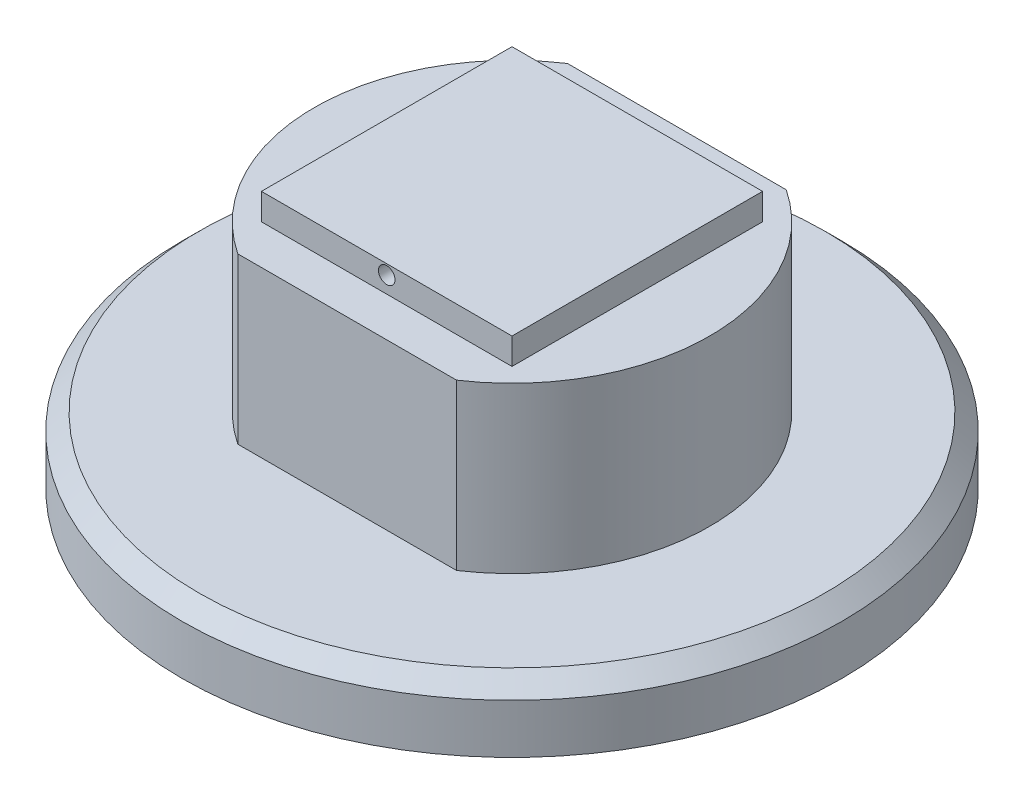
SolidWorks part; units mm, degrees
ref_plane "Frontale" through (0, 0, 0) normal (0, 0, 1) x (1, 0, 0)
ref_plane "Superiore" through (0, 0, 0) normal (0, 1, 0) x (1, 0, 0)
ref_plane "Destro" through (0, 0, 0) normal (1, 0, 0) x (0, 0, -1)
sketch "Schizzo1" plane through (0, 0, 0) normal (0, 1, 0) x (1, 0, 0)
  line L0 (-3.3166, 5) -> (3.3166, 5)
  line L1 (-6, 0) -> (6, 0) construction
  line L2 (-3.3166, -5) -> (3.3166, -5)
  arc A0 (-3.3166, 5) -> (-3.3166, -5) centre (0, 0) ccw
  arc A1 (3.3166, -5) -> (3.3166, 5) centre (0, 0) ccw
  dimension "D1" = 12
  dimension "D2" = 5
extrude "Estrusione-Estrusione1" add sketch "Schizzo1" along normal blind 5
sketch "Schizzo2" plane through (0, 5, 0) normal (0, 1, 0) x (1, 0, 0)
  line L0 (0, 5) -> (0, -5) construction
  line L1 (3.3166, 5) -> (-3.3166, 5) construction
  line L2 (-3.3166, -5) -> (3.3166, -5) construction
  line L3 (3.8, 3.8) -> (-3.8, 3.8)
  line L4 (-3.8, 3.8) -> (-3.8, -3.8)
  line L5 (-3.8, -3.8) -> (3.8, -3.8)
  line L6 (3.8, 3.8) -> (3.8, -3.8)
  line L7 (-6, 0) -> (6, 0) construction
  arc A0 (-3.3166, 5) -> (-3.3166, -5) centre (0, 0) ccw construction
  arc A1 (3.3166, -5) -> (3.3166, 5) centre (0, 0) ccw construction
  point P11 (0, -3.8)
  point P12 (0, 3.8)
  dimension "D1" = 3.8
  dimension "D2" = 3.8
  dimension "D3" = 3.8
extrude "Estrusione-Estrusione2" add sketch "Schizzo2" along normal blind 0.8
sketch "Schizzo3" plane through (0, 0, 3.8) normal (0, 0, 1) x (1, 0, 0)
  line L0 (0, 5.8) -> (0, 5) construction
  line L1 (-3.8, 5.8) -> (3.8, 5.8) construction
  line L2 (-3.3166, 5) -> (3.3166, 5) construction
  circle A0 centre (0, 5.5) radius 0.25
  dimension "D1" = 0.5
  dimension "D2" = 0.3
extrude "Taglio-Estrusione1" cut sketch "Schizzo3" against normal through all
sketch "Schizzo4" plane through (0, 0, 0) normal (0, -1, 0) x (1, 0, 0)
  circle A0 centre (0, 0) radius 10
  dimension "D1" = 20
extrude "Estrusione-Estrusione3" add sketch "Schizzo4" along normal blind 2
chamfer "Smusso1" distance 0.5 angle 45 1 edges at (0, 0, -10)
